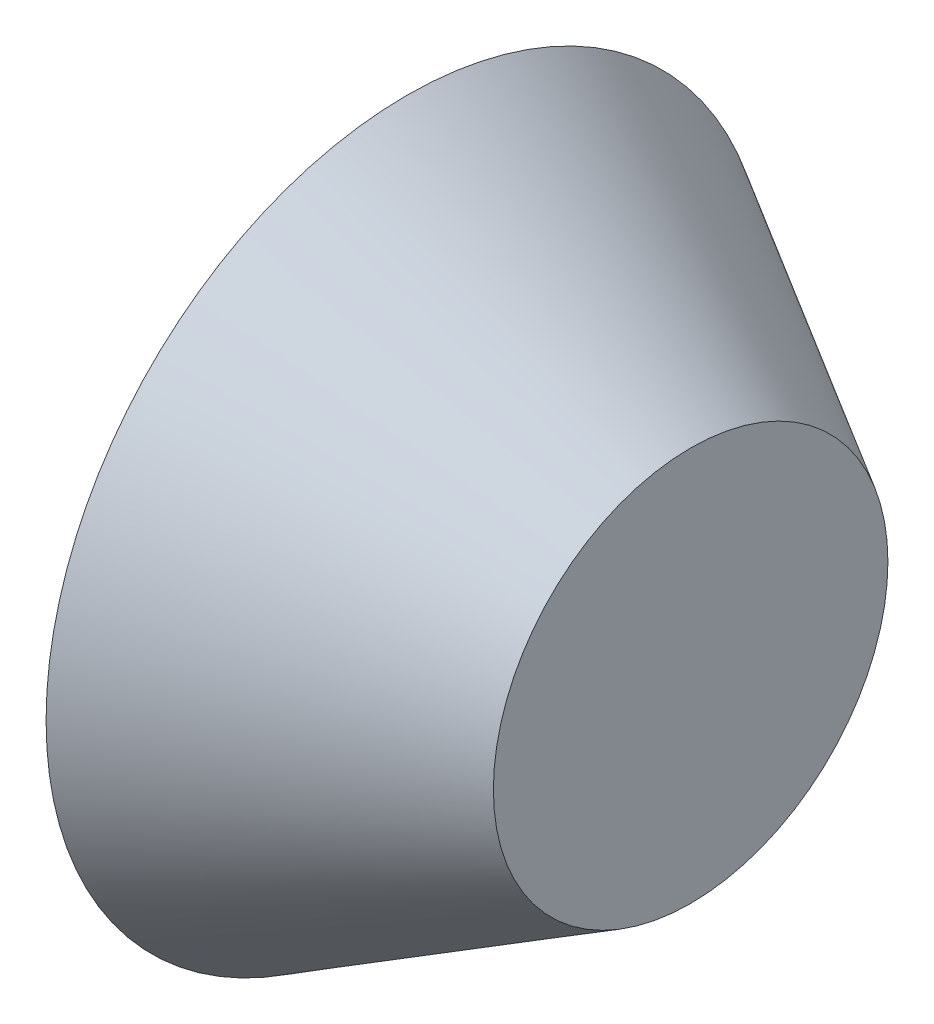
SolidWorks part; units mm, degrees
ref_plane "前视基准面" through (0, 0, 0) normal (0, 0, 1) x (1, 0, 0)
ref_plane "上视基准面" through (0, 0, 0) normal (0, 1, 0) x (1, 0, 0)
ref_plane "右视基准面" through (0, 0, 0) normal (1, 0, 0) x (0, 0, -1)
sketch "草图1" plane through (0, 0, 0) normal (0, 0, 1) x (1, 0, 0)
  line L0 (-17.0925, 0) -> (17.9589, 0) construction
  line L1 (0.1104, 14.6395) -> (11.6104, 8)
  line L2 (11.6104, 8) -> (11.6104, 0)
  line L3 (11.6104, 0) -> (8.6104, 0)
  line L4 (8.6104, 0) -> (8.6104, 6.2679)
  line L5 (8.6104, 6.2679) -> (0.1104, 11.1754)
  line L6 (0.1104, 11.1754) -> (0.1104, 14.6395)
  point P8 (4.3604, 8.7217)
  dimension "D1" = 11.5
  dimension "D2" = 3
  dimension "D3" = 30
  dimension "D4" = 3
  dimension "D5" = 8
revolve "旋转1" add sketch "草图1" angle 360 about L0
